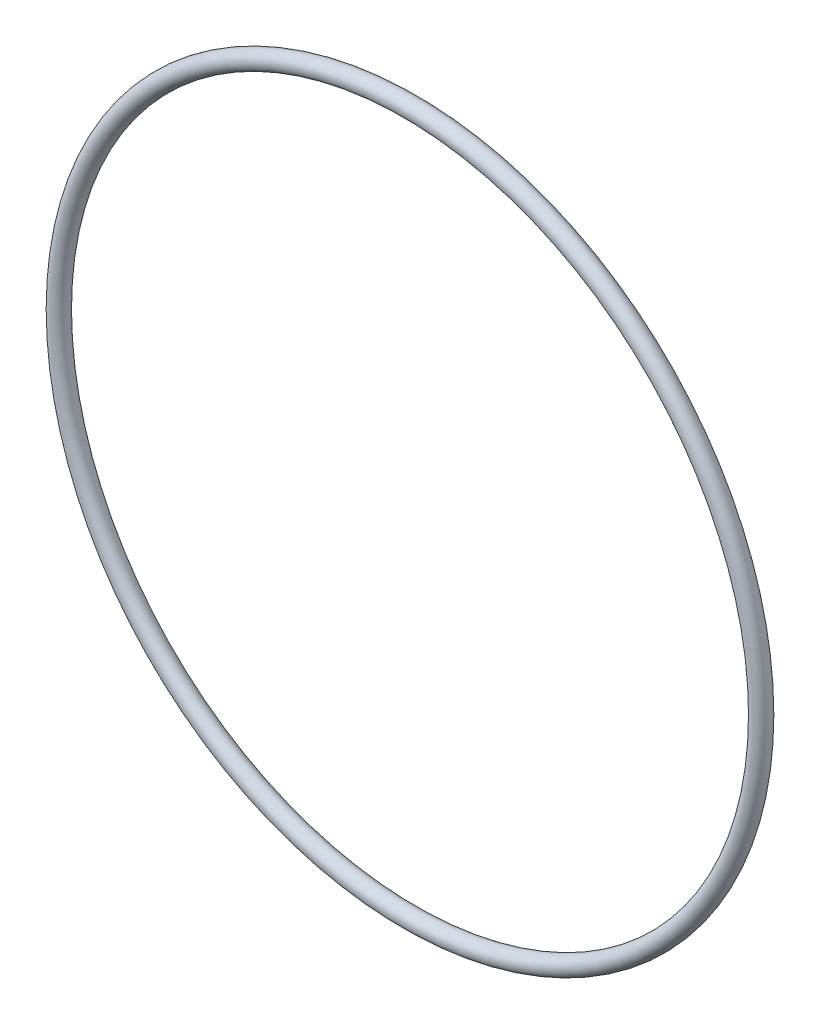
SolidWorks part; units mm, degrees
material "Silicon Rubber"
ref_plane "Front Plane" through (0, 0, 0) normal (0, 0, 1) x (1, 0, 0)
ref_plane "Top Plane" through (0, 0, 0) normal (0, 1, 0) x (1, 0, 0)
ref_plane "Right Plane" through (0, 0, 0) normal (1, 0, 0) x (0, 0, -1)
sketch "Sketch1" plane through (0, 0, 0) normal (0, 0, 1) x (1, 0, 0)
  circle A0 centre (0, 0) radius 59.69
  dimension "D1" = 119.38
sweep "Sweep1" add path "Sketch1" circular profile diameter 3.048 parameters "D3"=3.048
